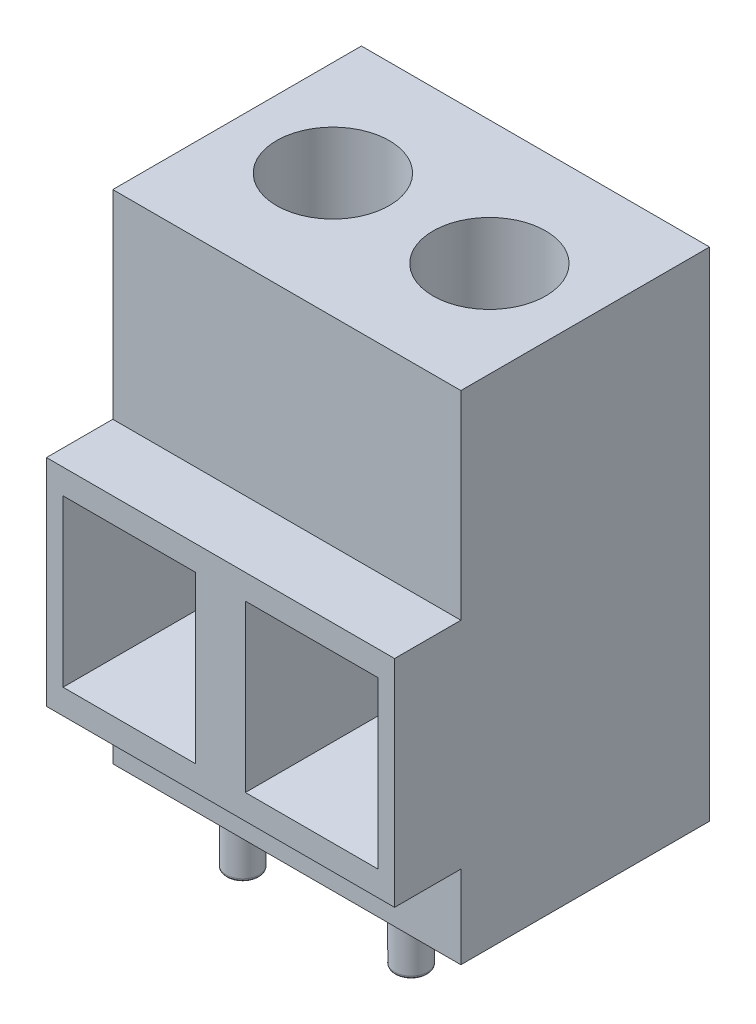
SolidWorks part; units mm, degrees
ref_plane "Спереди" through (0, 0, 0) normal (0, 0, 1) x (1, 0, 0)
ref_plane "Сверху" through (0, 0, 0) normal (0, 1, 0) x (1, 0, 0)
ref_plane "Справа" through (0, 0, 0) normal (1, 0, 0) x (0, 0, -1)
sketch "Эскиз1" plane through (0, 0, 0) normal (1, 0, 0) x (0, 0, -1)
  line L0 (0, 0) -> (0, 11.127) construction
  line L1 (0, 0) -> (24.076, 0) construction
  line L3 (-7.5, -15) -> (7.5, -15)
  line L4 (-7.5, -15) -> (-7.5, 15)
  line L5 (-7.5, 15) -> (7.5, 15)
  line L6 (7.5, -15) -> (7.5, 15)
  line L7 (-7.5, -15) -> (7.5, 15) construction
  line L8 (-7.5, 15) -> (7.5, -15) construction
  line L9 (-7.5, 3) -> (-11.5, 3)
  line L10 (-7.5, 3) -> (-7.5, -10)
  line L11 (-7.5, -10) -> (-11.5, -10)
  line L12 (-11.5, 3) -> (-11.5, -10)
  point P4 (0, 0)
  dimension "D1" = 15
  dimension "D2" = 30
  dimension "D3" = 5
  dimension "D4" = 13
  dimension "D5" = 4
extrude "Бобышка-Вытянуть1" add sketch "Эскиз1" along normal mid plane 21 contours L3 L6 L5 L4 | L9 L12 L11 L4
sketch "Эскиз3" plane through (0, 15, 0) normal (0, 1, 0) x (1, 0, 0)
  line L0 (-10.5, -7.5) -> (-10.5, 7.5) construction
  line L1 (10.5, -7.5) -> (10.5, 7.5) construction
  circle A0 centre (-4.72, 0) radius 3.4
  circle A2 centre (4.72, 0) radius 3.4
  dimension "D1" = 6.8
  dimension "D2" = 5.78
  dimension "D3" = 5.78
extrude "Вырез-Вытянуть1" cut sketch "Эскиз3" against normal blind 8
sketch "Эскиз4" plane through (0, 0, 11.5) normal (0, 0, 1) x (1, 0, 0)
  line L1 (10.5, 3) -> (10.5, -10) construction
  line L2 (11.0922, -3.5) -> (-10.4567, -3.5) construction
  line L3 (-8, -6) -> (-3, -6) construction
  line L4 (-8, -6) -> (-8, -1) construction
  line L5 (-8, -1) -> (-3, -1) construction
  line L6 (-3, -6) -> (-3, -1) construction
  line L7 (-8, -6) -> (-3, -1) construction
  line L12 (-9.5, -8.5) -> (-1.5, -8.5)
  line L13 (-9.5, -8.5) -> (-9.5, 1.5)
  line L14 (-9.5, 1.5) -> (-1.5, 1.5)
  line L15 (-1.5, -8.5) -> (-1.5, 1.5)
  line L16 (-9.5, -8.5) -> (-1.5, 1.5) construction
  line L17 (-9.5, 1.5) -> (-1.5, -8.5) construction
  line L18 (1.5, -8.5) -> (9.5, -8.5)
  line L19 (1.5, -8.5) -> (1.5, 1.5)
  line L20 (1.5, 1.5) -> (9.5, 1.5)
  line L21 (9.5, -8.5) -> (9.5, 1.5)
  line L22 (1.5, -8.5) -> (9.5, 1.5) construction
  line L23 (1.5, 1.5) -> (9.5, -8.5) construction
  line L24 (-8, -1) -> (-3, -6) construction
  point P0 (-5.5, -3.5)
  point P2 (-5.5, -3.5)
  point P7 (0.3178, -3.5)
  point P12 (5.5, -3.5)
  dimension "D2" = 10
  dimension "D3" = 8
  dimension "D1" = 8
  dimension "D4" = 10
  dimension "D5" = 5
  dimension "D6" = 5
  dimension "D7" = 3
  dimension "D8" = 1
extrude "Вырез-Вытянуть3" cut sketch "Эскиз4" against normal blind 16 draft 6
sketch "Эскиз7" plane through (0, 7, 0) normal (0, 1, 0) x (1, 0, 0)
  line L1 (-8.12, -0.5) -> (-1.357, -0.5)
  line L2 (-8.12, -0.5) -> (-8.12, 0.5)
  line L3 (-8.12, 0.5) -> (-1.357, 0.5)
  line L5 (-8.12, -0.5) -> (-1.3562, 0.4947) construction
  line L6 (-8.12, 0.5) -> (-1.3562, -0.4947) construction
  arc A0 (-1.357, -0.5) -> (-1.357, 0.5) centre (-4.72, 0) ccw
  circle A1 centre (-4.72, 0) radius 3.4
  arc A2 (-8.083, 0.5) -> (-8.083, -0.5) centre (-4.72, 0) ccw
  circle M5 centre (-4.72, 0) radius 3.4
  dimension "D3" = 1
  dimension "D1" = 0
extrude "Вырез-Вытянуть5" cut sketch "Эскиз7" against normal blind 1 contours L3 L1 M5
sketch "Эскиз8" plane through (0, 7, 0) normal (0, 1, 0) x (1, 0, 0)
  line L1 (1.357, 0.5) -> (8.083, 0.5)
  line L3 (1.357, -0.5) -> (8.083, -0.5)
  line L5 (1.3562, 0.4947) -> (8.0838, -0.4947) construction
  line L6 (1.3562, -0.4947) -> (8.0838, 0.4947) construction
  arc A0 (8.083, -0.5) -> (8.083, 0.5) centre (4.72, 0) ccw
  circle A1 centre (4.72, 0) radius 3.4
  arc A2 (1.357, 0.5) -> (1.357, -0.5) centre (4.72, 0) ccw
  point P0 (4.72, 0)
  dimension "D3" = 0
extrude "Вырез-Вытянуть6" cut sketch "Эскиз8" against normal blind 1 contours A2 L3 A0 L1
sketch "Эскиз9" plane through (0, -15, 0) normal (0, -1, 0) x (1, 0, 0)
  line L1 (-5.08, 5.08) -> (5.08, 5.08) construction
  line L2 (-5.08, 5.08) -> (-5.08, -5.08) construction
  line L3 (-5.08, -5.08) -> (5.08, -5.08) construction
  line L4 (5.08, 5.08) -> (5.08, -5.08) construction
  line L5 (-5.08, 5.08) -> (5.08, -5.08) construction
  line L6 (-5.08, -5.08) -> (5.08, 5.08) construction
  circle A0 centre (-5.08, 5.08) radius 1
  circle A1 centre (5.08, 5.08) radius 1
  circle A2 centre (5.08, -5.08) radius 1
  circle A3 centre (-5.08, -5.08) radius 1
  point P0 (0, 0)
  dimension "D3" = 2
  dimension "D1" = 10.16
  dimension "D2" = 10.16
extrude "Бобышка-Вытянуть2" add sketch "Эскиз9" along normal blind 4
fillet "Скругление3" radius 0.2 4 edges at (5.08, -19, -6.08) (-5.08, -19, -6.08) (5.08, -19, 4.08) (-5.08, -19, 4.08)
